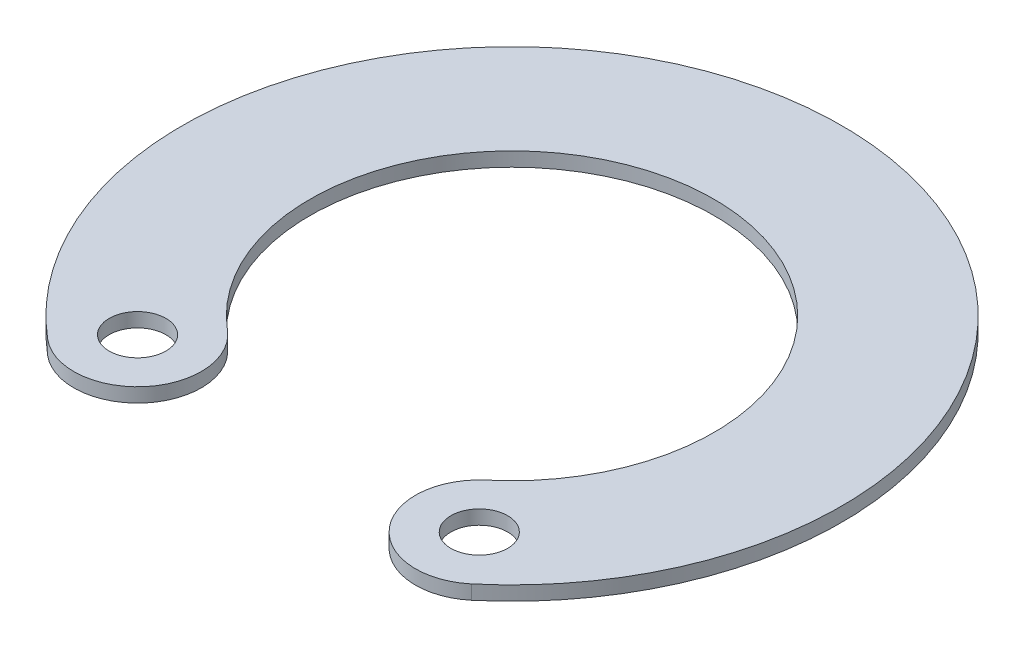
SolidWorks part; units mm, degrees
material "Cast Alloy Steel"
ref_plane "Front Plane" through (0, 0, 0) normal (0, 0, 1) x (1, 0, 0)
ref_plane "Top Plane" through (0, 0, 0) normal (0, 1, 0) x (1, 0, 0)
ref_plane "Right Plane" through (0, 0, 0) normal (1, 0, 0) x (0, 0, -1)
sketch "Sketch2" plane through (0, 0, 0) normal (0, 1, 0) x (1, 0, 0)
  line L0 (-2.4105, -2.8727) -> (0, 0) construction
  line L1 (2.4105, -2.8727) -> (0, 0) construction
  line L2 (0, 0) -> (0, -3.6679) construction
  arc A0 (-2.4105, -2.8727) -> (2.4105, -2.8727) centre (0, 0) cw construction
  arc A1 (2.989, -3.5621) -> (-2.989, -3.5621) centre (0, 0) ccw
  arc A2 (1.8319, -2.1832) -> (-1.8319, -2.1832) centre (0, 0) ccw
  arc A3 (1.8319, -2.1832) -> (2.989, -3.5621) centre (2.4105, -2.8727) ccw
  arc A4 (-2.989, -3.5621) -> (-1.8319, -2.1832) centre (-2.4105, -2.8727) ccw
  circle A5 centre (-2.4105, -2.8727) radius 0.4
  circle A6 centre (2.4105, -2.8727) radius 0.4
  point P4 (0, 3.75)
  dimension "D1" = 0.9
  dimension "D2" = 4.65
  dimension "D3" = 0.8
  dimension "D4" = 80
extrude "Boss-Extrude1" add sketch "Sketch2" along normal blind 0.2
